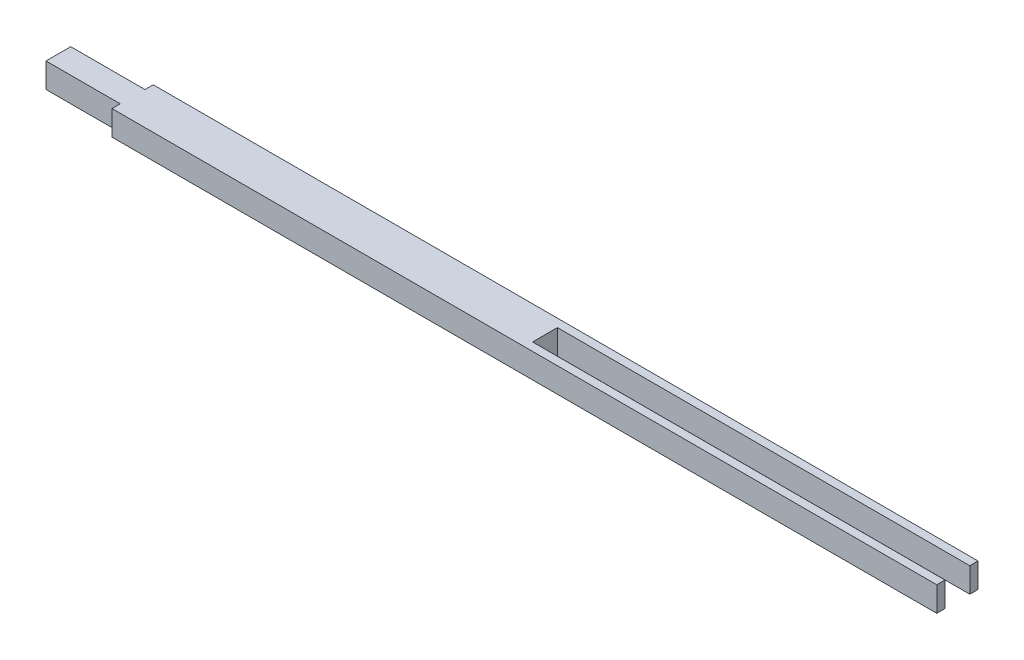
SolidWorks part; units mm, degrees
ref_plane "Front Plane" through (0, 0, 0) normal (0, 0, 1) x (1, 0, 0)
ref_plane "Top Plane" through (0, 0, 0) normal (0, 1, 0) x (1, 0, 0)
ref_plane "Right Plane" through (0, 0, 0) normal (1, 0, 0) x (0, 0, -1)
sketch "Sketch1" plane through (0, 0, 0) normal (0, 1, 0) x (1, 0, 0)
  line L1 (-50, -2.5) -> (50, -2.5)
  line L2 (-50, -2.5) -> (-50, 2.5)
  line L3 (-50, 2.5) -> (50, 2.5)
  line L4 (50, -2.5) -> (50, 2.5)
  line L5 (0, 2.5) -> (0, -2.5) construction
  line L6 (-50, 0) -> (50, 0) construction
  point P0 (0, 0)
  dimension "D1" = 100
  dimension "D2" = 5
extrude "Boss-Extrude1" add sketch "Sketch1" along normal blind 3
sketch "Sketch2" plane through (0, 3, 0) normal (0, 1, 0) x (1, 0, 0)
  line L0 (0, 0) -> (50, 0) construction
  line L1 (50, -2.5) -> (50, 2.5) construction
  line L3 (0, -1.505) -> (50, -1.505)
  line L4 (0, -1.505) -> (0, 1.505)
  line L5 (0, 1.505) -> (50, 1.505)
  line L6 (50, -1.505) -> (50, 1.505)
  line L7 (25, 1.505) -> (25, -1.505) construction
  line L8 (0, 0) -> (50, 0) construction
  point P4 (25, 0)
  dimension "D1" = 3.01
extrude "Cut-Extrude1" cut sketch "Sketch2" against normal blind 3
sketch "Sketch3" plane through (0, 3, 0) normal (0, 1, 0) x (1, 0, 0)
  line L0 (-50, 2.5) -> (-50, -2.5) construction
  line L1 (-59, -1.5) -> (-41, -1.5)
  line L2 (-59, -1.5) -> (-59, 1.5)
  line L3 (-59, 1.5) -> (-41, 1.5)
  line L4 (-41, -1.5) -> (-41, 1.5)
  line L5 (-50, 1.5) -> (-50, -1.5) construction
  line L6 (-59, 0) -> (-41, 0) construction
  point P0 (-50, 0)
  dimension "D1" = 3
  dimension "D2" = 18
extrude "Boss-Extrude2" add sketch "Sketch3" against normal blind 3
